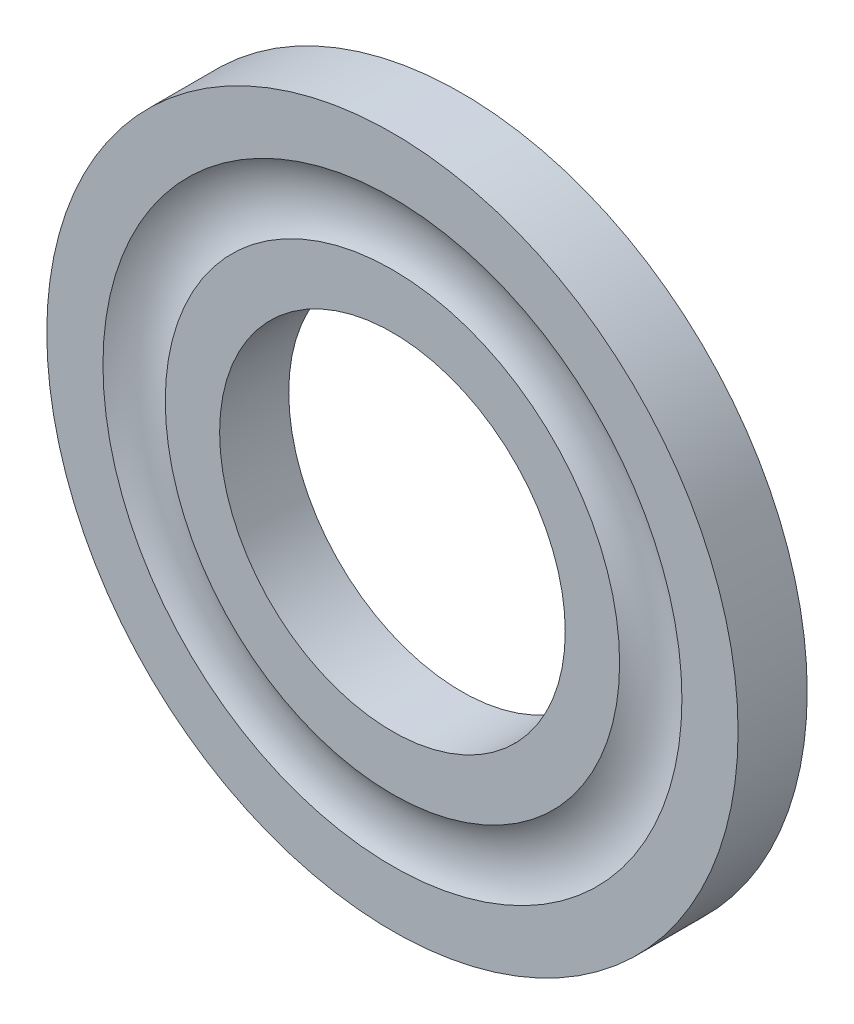
SolidWorks part; units mm, degrees
ref_plane "Спереди" through (0, 0, 0) normal (0, 0, 1) x (1, 0, 0)
ref_plane "Сверху" through (0, 0, 0) normal (0, 1, 0) x (1, 0, 0)
ref_plane "Справа" through (0, 0, 0) normal (1, 0, 0) x (0, 0, -1)
sketch "Эскиз1" plane through (0, 0, 0) normal (0, 0, 1) x (1, 0, 0)
  circle A0 centre (0, 0) radius 10
  circle A1 centre (0, 0) radius 20
  dimension "D1" = 20
  dimension "D2" = 40
extrude "Вытянуть1" add sketch "Эскиз1" along normal blind 4
sketch "Эскиз2" plane through (0, 0, 4) normal (0, 0, 1) x (1, 0, 0)
  circle A0 centre (0, 0) radius 15
  circle A1 centre (0, 0) radius 10 construction
  dimension "D1" = 30
sketch "Эскиз3" plane through (0, 0, 0) normal (0, 1, 0) x (1, 0, 0)
  circle A0 centre (14.9478, -7) radius 3.5
  dimension "D1" = 7
  dimension "D2" = 14.9478
  dimension "D3" = 7
sweep "Вырез-По траектории1" cut profiles "Эскиз3" path "Эскиз2"
